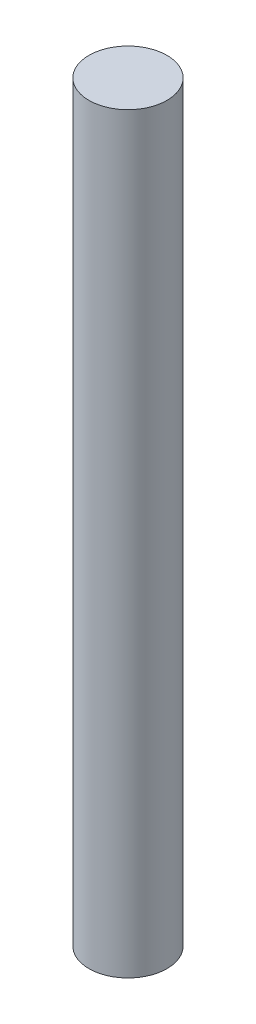
SolidWorks part; units mm, degrees
ref_plane "Piano frontale" through (0, 0, 0) normal (0, 0, 1) x (1, 0, 0)
ref_plane "Piano superiore" through (0, 0, 0) normal (0, 1, 0) x (1, 0, 0)
ref_plane "Piano destro" through (0, 0, 0) normal (1, 0, 0) x (0, 0, -1)
sketch "Schizzo2" plane through (0, 0, 0) normal (0, 1, 0) x (1, 0, 0)
  circle A0 centre (0, 0) radius 2.495
  dimension "D1" = 4.99
extrude "Estrusione-Estrusione1" add sketch "Schizzo2" along normal blind 48.09
sketch "Schizzo3" plane through (0, 0, 0) normal (0, 0, 1) x (1, 0, 0)
  line L0 (-2.495, 48.09) -> (-2.495, 0) construction
  line L1 (-2.495, 47.255) -> (-1.645, 47.255)
  line L2 (-2.495, 47.255) -> (-2.495, 43.245)
  line L3 (-2.495, 43.245) -> (-1.645, 43.245)
  line L4 (-1.645, 47.255) -> (-1.645, 43.245)
  line L5 (-2.495, 24.045) -> (2.495, 24.045) construction
  line L6 (2.495, 0) -> (2.495, 48.09) construction
  line L7 (-1.645, 0.835) -> (-1.645, 4.845)
  line L8 (-2.495, 4.845) -> (-1.645, 4.845)
  line L9 (-2.495, 0.835) -> (-2.495, 4.845)
  line L10 (-2.495, 0.835) -> (-1.645, 0.835)
  dimension "D1" = 4.01
  dimension "D2" = 38.4
  dimension "D3" = 0.85
extrude "Taglio-Estrusione1" cut sketch "Schizzo3" against normal through all and the other way through all
